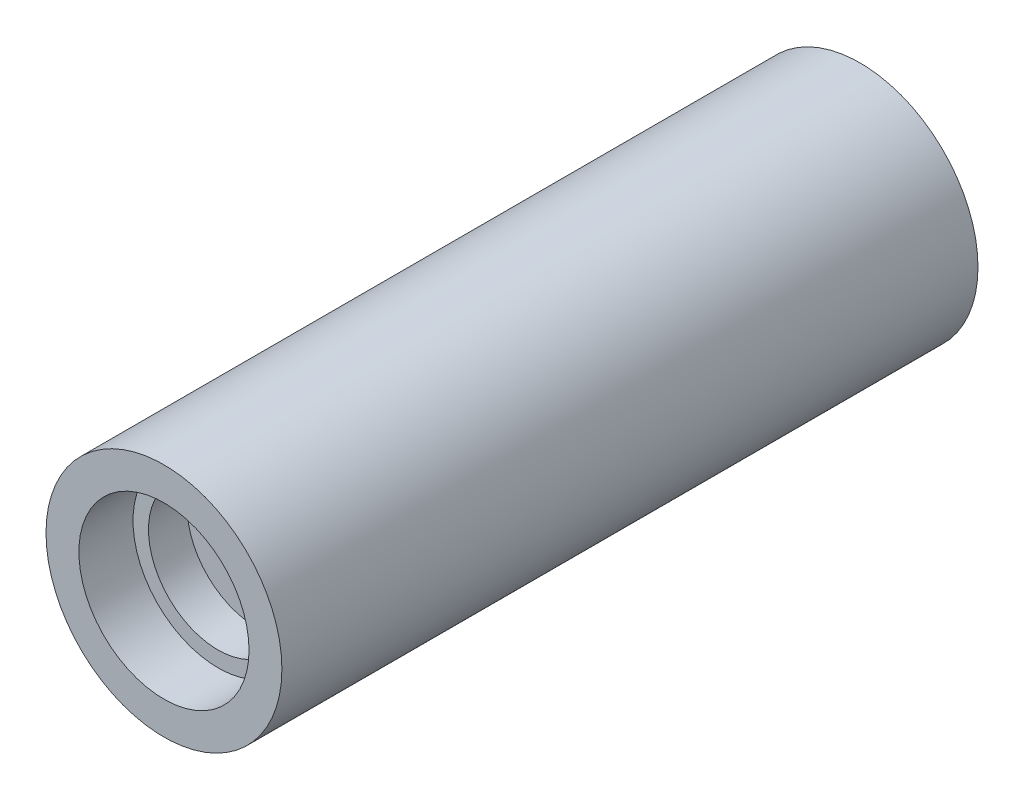
SolidWorks part; units mm, degrees
ref_plane "Plan de face" through (0, 0, 0) normal (0, 0, 1) x (1, 0, 0)
ref_plane "Plan de dessus" through (0, 0, 0) normal (0, 1, 0) x (1, 0, 0)
ref_plane "Plan de droite" through (0, 0, 0) normal (1, 0, 0) x (0, 0, -1)
sketch "Esquisse1" plane through (0, 0, 0) normal (0, 0, 1) x (1, 0, 0)
  circle A0 centre (0, 0) radius 15.25
  dimension "D1" = 30.5
extrude "Boss.-Extru.1" add sketch "Esquisse1" along normal blind 90
sketch "Esquisse2" plane through (0, 0, 90) normal (0, 0, 1) x (1, 0, 0)
  circle A0 centre (0, 0) radius 11
  dimension "D1" = 22
extrude "Enlèv. mat.-Extru.1" cut sketch "Esquisse2" against normal blind 7
sketch "Esquisse3" plane through (0, 0, 83) normal (0, 0, 1) x (1, 0, 0)
  circle A0 centre (0, 0) radius 9
  circle A1 centre (0, 0) radius 11 construction
  dimension "D1" = 2
extrude "Enlèv. mat.-Extru.2" cut sketch "Esquisse3" against normal blind 5
ref_plane "Plan1" through (0, 0, 45) normal (0, 0, 1) x (1, 0, 0)
mirror "Symétrie1" about plane through (0, 0, 45) normal (0, 0, 1) of "Enlèv. mat.-Extru.2", "Enlèv. mat.-Extru.1"
